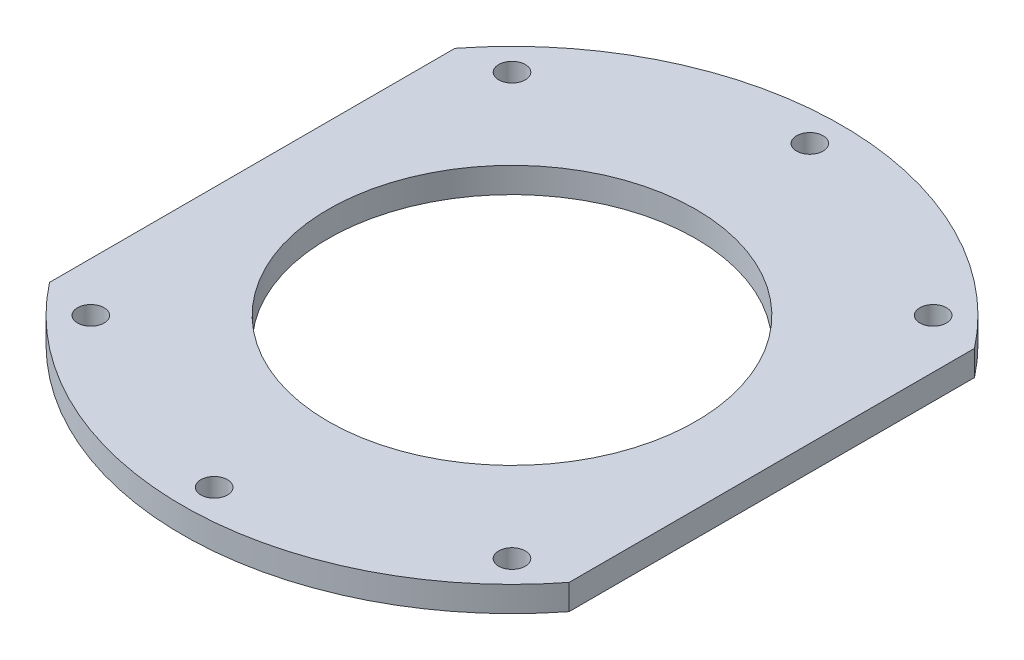
SolidWorks part; units mm, degrees
ref_plane "前视基准面" through (0, 0, 0) normal (0, 0, 1) x (1, 0, 0)
ref_plane "上视基准面" through (0, 0, 0) normal (0, 1, 0) x (1, 0, 0)
ref_plane "右视基准面" through (0, 0, 0) normal (1, 0, 0) x (0, 0, -1)
sketch "草图1" plane through (0, 0, 0) normal (0, 1, 0) x (1, 0, 0)
  circle A0 centre (0, 0) radius 29
  circle A1 centre (0, 0) radius 52
  circle A2 centre (47, 0) radius 2.1
  circle A3 centre (33.234, -33.234) radius 2.1
  circle A4 centre (0, -47) radius 2.1
  circle A5 centre (-33.234, -33.234) radius 2.1
  circle A6 centre (-47, 0) radius 2.1
  circle A7 centre (-33.234, 33.234) radius 2.1
  circle A8 centre (0, 47) radius 2.1
  circle A9 centre (33.234, 33.234) radius 2.1
  circle A10 centre (0, 0) radius 43 construction
  point P6 (52, 0)
  point P9 (43, 0)
  dimension "D1" = 58
  dimension "D2" = 86
  dimension "D3" = 4
  dimension "D4" = 4.2
  dimension "D7" = 5
  dimension "D5" = 8
extrude "凸台-拉伸1" add sketch "草图1" along normal blind 4
sketch "草图2" plane through (0, 4, 0) normal (0, 1, 0) x (1, 0, 0)
  line L1 (-41, -55.0176) -> (41, -55.0176)
  line L2 (-41, -55.0176) -> (-41, 55.0176)
  line L3 (-41, 55.0176) -> (41, 55.0176)
  line L4 (41, -55.0176) -> (41, 55.0176)
  line L5 (-41, -55.0176) -> (41, 55.0176) construction
  line L6 (-41, 55.0176) -> (41, -55.0176) construction
  point P0 (0, 0)
  dimension "D1" = 82
extrude "切除-拉伸-薄壁1" cut sketch "草图2" against normal blind 4 thin
